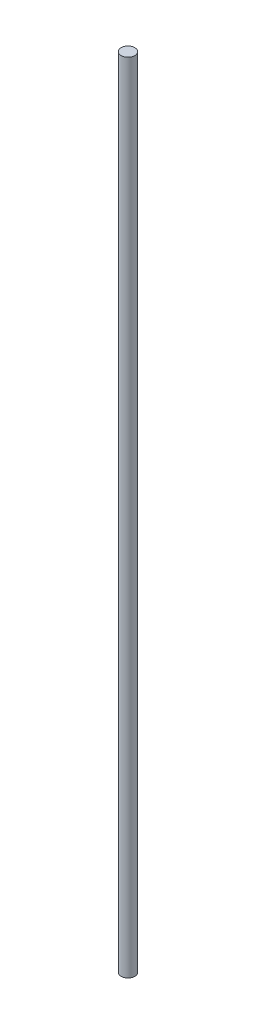
SolidWorks part; units mm, degrees
ref_plane "Front Plane" through (0, 0, 0) normal (0, 0, 1) x (1, 0, 0)
ref_plane "Top Plane" through (0, 0, 0) normal (0, 1, 0) x (1, 0, 0)
ref_plane "Right Plane" through (0, 0, 0) normal (1, 0, 0) x (0, 0, -1)
sketch "Sketch1" plane through (0, 0, 0) normal (0, 1, 0) x (1, 0, 0)
  circle A0 centre (0, 0) radius 2.15
  dimension "D1" = 4.3
extrude "Boss-Extrude1" add sketch "Sketch1" along normal blind 250 contours A0
